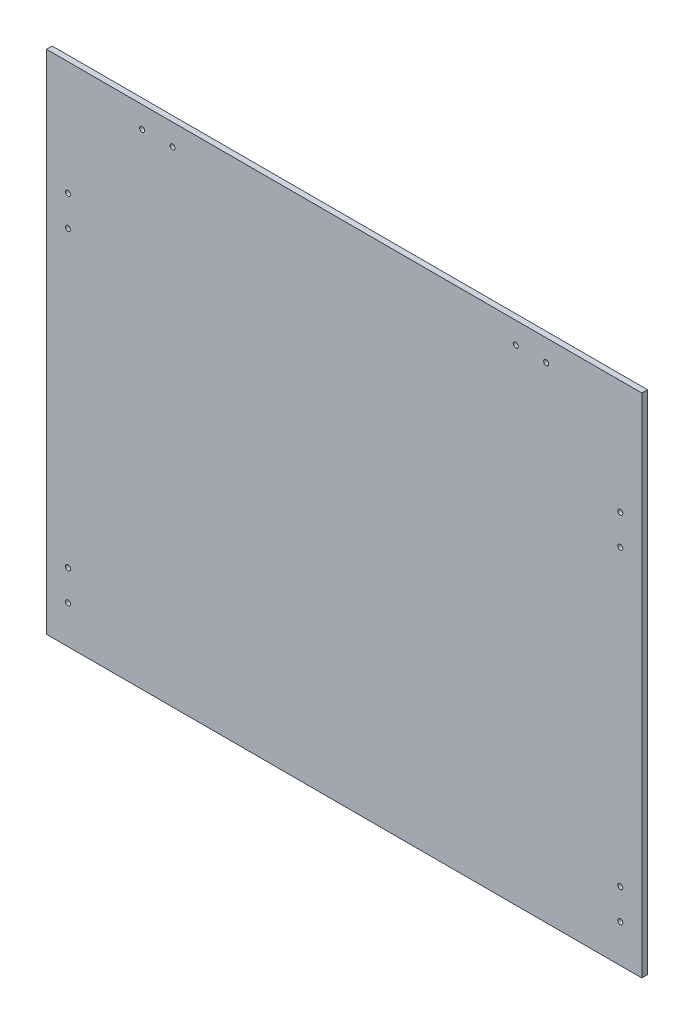
SolidWorks part; units mm, degrees
material "ABS PC"
ref_plane "前视基准面" through (0, 0, 0) normal (0, 0, 1) x (1, 0, 0)
ref_plane "上视基准面" through (0, 0, 0) normal (0, 1, 0) x (1, 0, 0)
ref_plane "右视基准面" through (0, 0, 0) normal (1, 0, 0) x (0, 0, -1)
sketch "草图1" plane through (0, 0, 0) normal (0, 0, 1) x (1, 0, 0)
  line L1 (0, 0) -> (470, 0)
  line L2 (0, 0) -> (0, 400)
  line L3 (0, 400) -> (470, 400)
  line L4 (470, 0) -> (470, 400)
  dimension "D1" = 470
  dimension "D2" = 400
extrude "凸台-拉伸1" add sketch "草图1" along normal blind 4.5
sketch "草图2" plane through (0, 0, 4.5) normal (0, 0, 1) x (1, 0, 0)
  line L0 (235, 400) -> (235, 0) construction
  line L1 (470, 400) -> (0, 400) construction
  line L2 (0, 0) -> (470, 0) construction
  line L3 (75.5, 383) -> (99.5, 383) construction
  line L4 (17, 310) -> (17, 286) construction
  line L5 (17, 54) -> (17, 30) construction
  line L6 (0, 400) -> (0, 0) construction
  line L7 (453, 54) -> (453, 30) construction
  line L8 (453, 310) -> (453, 286) construction
  line L9 (394.5, 383) -> (370.5, 383) construction
  circle A0 centre (99.5, 383) radius 2
  circle A1 centre (75.5, 383) radius 2
  circle A2 centre (17, 310) radius 2
  circle A3 centre (17, 286) radius 2
  circle A4 centre (17, 54) radius 2
  circle A5 centre (17, 30) radius 2
  circle A6 centre (453, 30) radius 2
  circle A7 centre (453, 54) radius 2
  circle A8 centre (453, 286) radius 2
  circle A9 centre (453, 310) radius 2
  circle A10 centre (394.5, 383) radius 2
  circle A11 centre (370.5, 383) radius 2
  dimension "D9" = 4
  dimension "D1" = 17
  dimension "D2" = 17
  dimension "D3" = 90
  dimension "D4" = 30
  dimension "D5" = 24
  dimension "D6" = 24
  dimension "D7" = 24
  dimension "D8" = 75.5
extrude "切除-拉伸1" cut sketch "草图2" against normal blind 10
